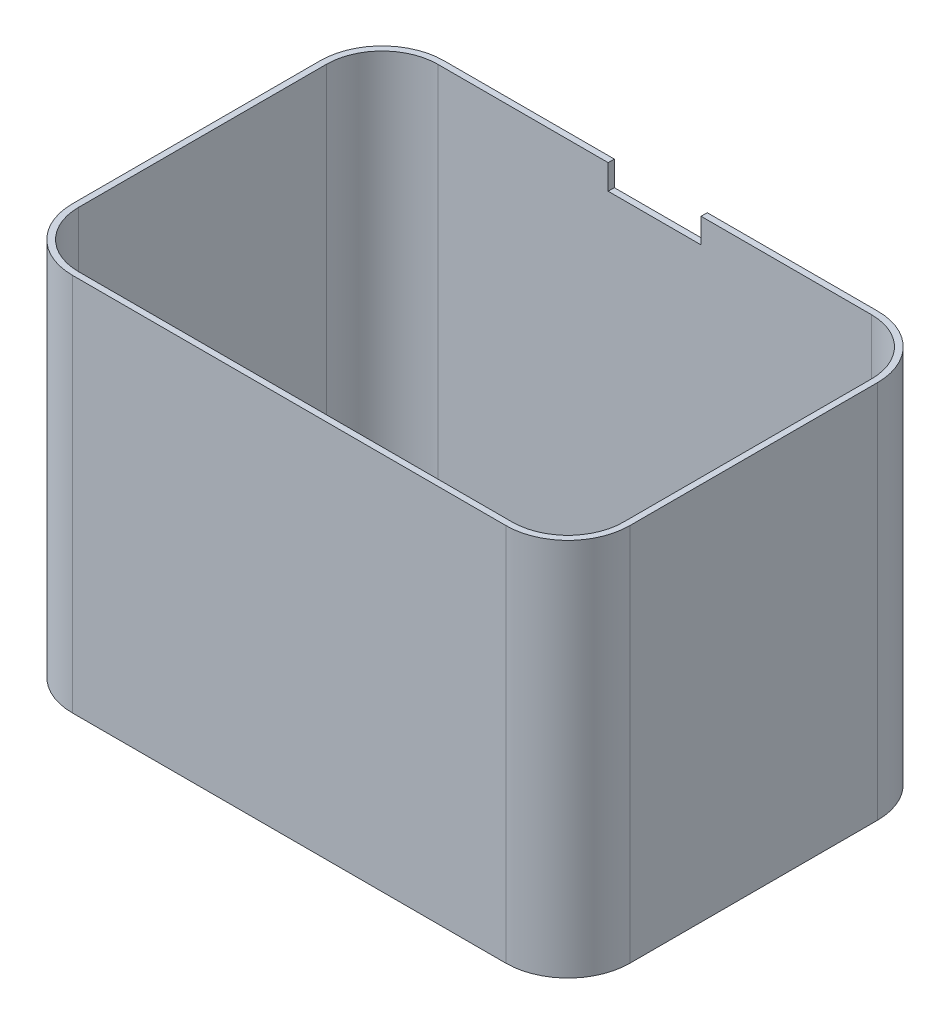
SolidWorks part; units mm, degrees
ref_plane "前视基准面" through (0, 0, 0) normal (0, 0, 1) x (1, 0, 0)
ref_plane "上视基准面" through (0, 0, 0) normal (0, 1, 0) x (1, 0, 0)
ref_plane "右视基准面" through (0, 0, 0) normal (1, 0, 0) x (0, 0, -1)
sketch "草图1" plane through (0, 0, 0) normal (0, 1, 0) x (1, 0, 0)
  line L1 (-35, 30) -> (35, 30)
  line L2 (-45, 20) -> (-45, -20)
  line L3 (-35, -30) -> (35, -30)
  line L4 (45, 20) -> (45, -20)
  line L5 (-45, 30) -> (45, -30) construction
  line L6 (-45, -30) -> (45, 30) construction
  arc A0 (-35, 30) -> (-45, 20) centre (-35, 20) ccw
  arc A1 (35, 30) -> (45, 20) centre (35, 20) cw
  arc A2 (35, -30) -> (45, -20) centre (35, -20) ccw
  arc A3 (-45, -20) -> (-35, -30) centre (-35, -20) ccw
  point P0 (0, 0)
  dimension "D3" = 10
  dimension "D1" = 90
  dimension "D2" = 60
extrude "凸台-拉伸1" add sketch "草图1" along normal blind 1.2
sketch "草图2" plane through (0, 1.2, 0) normal (0, 1, 0) x (1, 0, 0)
  line L4 (45, -20) -> (45, 20)
  line L5 (35, 30) -> (-35, 30)
  line L6 (-45, 20) -> (-45, -20)
  line L7 (-35, -30) -> (35, -30)
  line L8 (45, -20) -> (45, 20)
  line L9 (35, 30) -> (-35, 30)
  line L10 (-45, 20) -> (-45, -20)
  line L11 (-35, -30) -> (35, -30)
  line L16 (44, -20) -> (44, 20)
  line L17 (35, 29) -> (-35, 29)
  line L18 (-44, 20) -> (-44, -20)
  line L19 (-35, -29) -> (35, -29)
  line L20 (44, -20) -> (44, 20)
  line L21 (35, 29) -> (-35, 29)
  line L22 (-44, 20) -> (-44, -20)
  line L23 (-35, -29) -> (35, -29)
  arc A4 (-35, 30) -> (-45, 20) centre (-35, 20) ccw
  arc A5 (-35, 30) -> (-45, 20) centre (-35, 20) ccw
  arc A6 (-45, -20) -> (-35, -30) centre (-35, -20) ccw
  arc A7 (-45, -20) -> (-35, -30) centre (-35, -20) ccw
  arc A8 (35, -30) -> (45, -20) centre (35, -20) ccw
  arc A9 (35, -30) -> (45, -20) centre (35, -20) ccw
  arc A10 (45, 20) -> (35, 30) centre (35, 20) ccw
  arc A11 (45, 20) -> (35, 30) centre (35, 20) ccw
  arc A12 (-35, 29) -> (-44, 20) centre (-35, 20) ccw
  arc A13 (-35, 29) -> (-44, 20) centre (-35, 20) ccw
  arc A14 (-44, -20) -> (-35, -29) centre (-35, -20) ccw
  arc A15 (-44, -20) -> (-35, -29) centre (-35, -20) ccw
  arc A16 (35, -29) -> (44, -20) centre (35, -20) ccw
  arc A17 (35, -29) -> (44, -20) centre (35, -20) ccw
  arc A18 (44, 20) -> (35, 29) centre (35, 20) ccw
  arc A19 (44, 20) -> (35, 29) centre (35, 20) ccw
  dimension "D1" = 0
  dimension "D2" = 1
extrude "凸台-拉伸2" add sketch "草图2" along normal blind 60
sketch "草图5" plane through (0, 0, -30) normal (0, 0, -1) x (-1, 0, 0)
  line L0 (-35, 61.2) -> (35, 61.2) construction
  line L1 (-7.5, 65.2) -> (7.5, 65.2)
  line L2 (-7.5, 65.2) -> (-7.5, 57.2)
  line L3 (-7.5, 57.2) -> (7.5, 57.2)
  line L4 (7.5, 65.2) -> (7.5, 57.2)
  line L5 (-7.5, 65.2) -> (7.5, 57.2) construction
  line L6 (-7.5, 57.2) -> (7.5, 65.2) construction
  point P0 (0, 61.2)
  dimension "D1" = 15
  dimension "D2" = 8
extrude "切除-拉伸1" cut sketch "草图5" against normal blind 1.5
